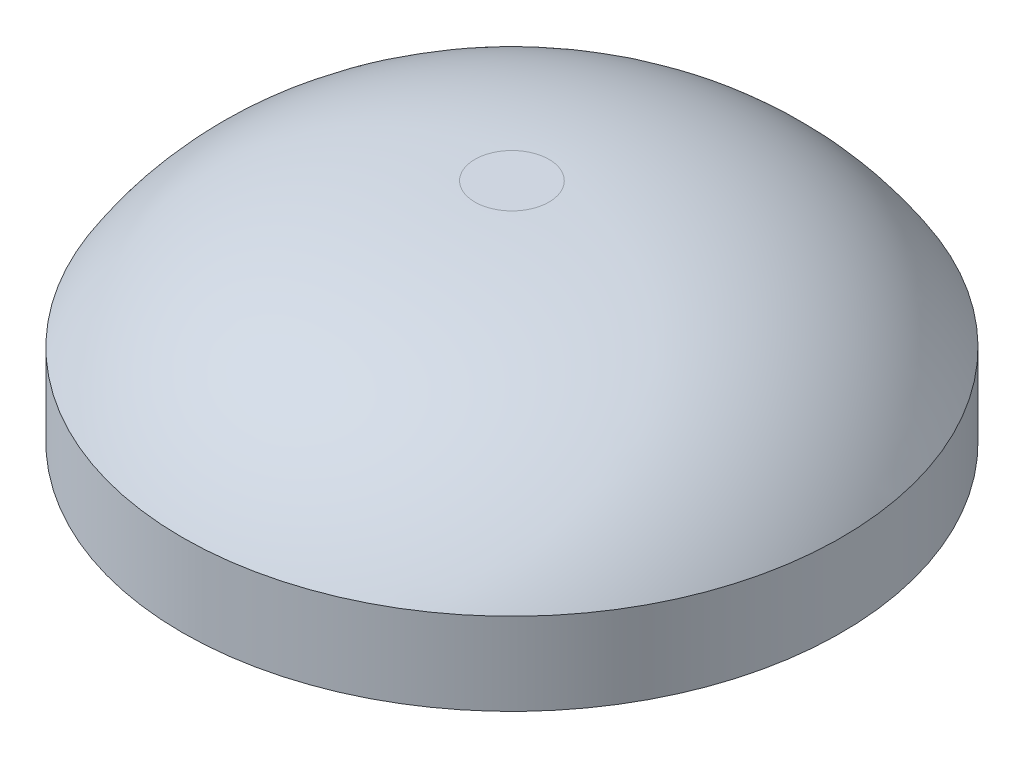
SolidWorks part; units mm, degrees
ref_plane "Plan de face" through (0, 0, 0) normal (0, 0, 1) x (1, 0, 0)
ref_plane "Plan de dessus" through (0, 0, 0) normal (0, 1, 0) x (1, 0, 0)
ref_plane "Plan de droite" through (0, 0, 0) normal (1, 0, 0) x (0, 0, -1)
sketch "Esquisse1" plane through (0, 0, 0) normal (0, 0, 1) x (1, 0, 0)
  line L0 (0, 1) -> (4, 1)
  line L1 (0, 0) -> (4, 0)
  line L2 (0, 0) -> (0, 2.75)
  line L3 (0, 2.75) -> (4, 2.75)
  line L4 (4, 0) -> (4, 2.75)
  spline S0 degree 2 poles (0, 2.75) (3.048, 2.8321) (4.1491, 0.7409) knots 0 0 0 1 1 1
  dimension "D1" = 4
  dimension "D2" = 2.75
  dimension "D3" = 1
ref_axis "Axe1" through (0, 2.75, 0) along (0, -1, 0)
revolve "Révolution1" add sketch "Esquisse1" angle 360 about axis through (0, 2.75, 0) along (0, -1, 0)
